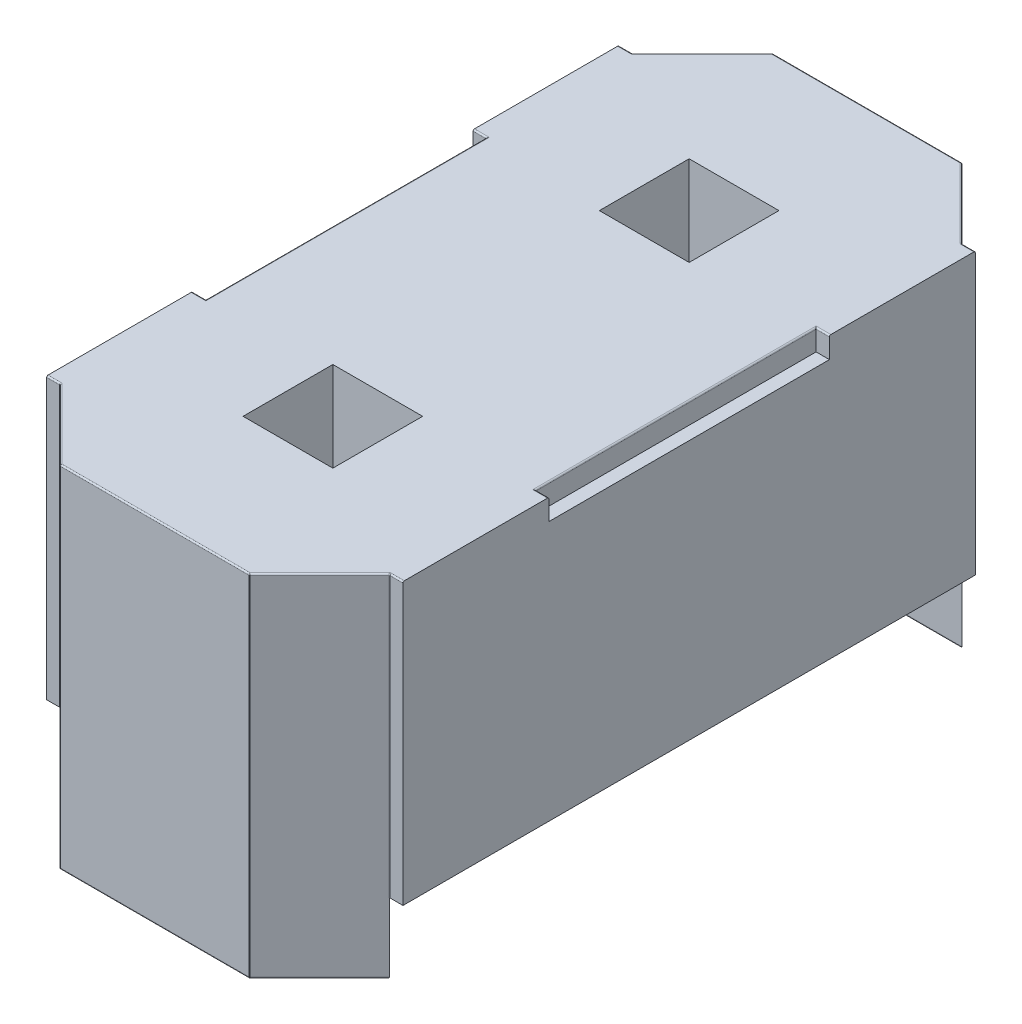
SolidWorks part; units mm, degrees
ref_plane "前视基准面" through (0, 0, 0) normal (0, 0, 1) x (1, 0, 0)
ref_plane "上视基准面" through (0, 0, 0) normal (0, 1, 0) x (1, 0, 0)
ref_plane "右视基准面" through (0, 0, 0) normal (1, 0, 0) x (0, 0, -1)
sketch "Sketch5" plane through (0, 0, 0) normal (0, 1, 0) x (1, 0, 0)
  line L0 (-0.675, 2.54) -> (-1.175, 2.04)
  line L1 (-0.675, 2.54) -> (0.675, 2.54)
  line L2 (-1.175, 2.04) -> (-1.175, -2.04)
  line L3 (-0.675, -2.54) -> (0.675, -2.54)
  line L4 (1.175, 2.04) -> (1.175, -2.04)
  line L7 (0, 2.54) -> (0, -2.54) construction
  line L8 (0.675, 2.54) -> (1.175, 2.04)
  line L9 (-1.175, 0) -> (1.175, 0) construction
  line L10 (0.675, -2.54) -> (1.175, -2.04)
  line L11 (-0.675, -2.54) -> (-1.175, -2.04)
  point P0 (0, 0)
  point P20 (0, 0)
  point P22 (0, -2.54)
  dimension "D1" = 2.35
  dimension "D2" = 5.08
  dimension "D3" = 0.5
  dimension "D4" = 0.5
extrude "Boss-Extrude1" add sketch "Sketch5" along normal blind 2.5
sketch "Sketch7" plane through (0, 2.5, 0) normal (0, 1, 0) x (1, 0, 0)
  line L0 (0, 2.54) -> (0, -2.54) construction
  line L1 (-0.32, 1.59) -> (0.32, 1.59)
  line L2 (-0.32, 1.59) -> (-0.32, 0.95)
  line L3 (-0.32, 0.95) -> (0.32, 0.95)
  line L4 (0.32, 1.59) -> (0.32, 0.95)
  line L5 (-0.32, 1.59) -> (0.32, 0.95) construction
  line L6 (-0.32, 0.95) -> (0.32, 1.59) construction
  line L7 (0.675, 2.54) -> (-0.675, 2.54) construction
  line L8 (-0.675, -2.54) -> (0.675, -2.54) construction
  line L9 (-1.175, 0) -> (1.175, 0) construction
  line L10 (-1.175, 2.04) -> (-1.175, -2.04) construction
  line L11 (1.175, -2.04) -> (1.175, 2.04) construction
  line L12 (-0.32, -0.95) -> (0.32, -0.95)
  line L13 (0.32, -1.59) -> (0.32, -0.95)
  line L14 (-0.32, -1.59) -> (0.32, -1.59)
  line L15 (-0.32, -1.59) -> (-0.32, -0.95)
  line L16 (-0.32, -0.95) -> (0.32, -1.59) construction
  line L17 (-0.32, -1.59) -> (0.32, -0.95) construction
  point P0 (0, 1.27)
  point P17 (0, 0)
  dimension "D1" = 0.64
  dimension "D2" = 0.64
  dimension "D3" = 1.27
extrude "Cut-Extrude1" cut sketch "Sketch7" against normal through all
sketch "Sketch8" plane through (0, 2.5, 0) normal (0, 1, 0) x (1, 0, 0)
  line L0 (0, 2.54) -> (0, -2.54) construction
  line L1 (-1.27, -2.04) -> (-1.175, -2.04)
  line L2 (-1.27, -2.04) -> (-1.27, 2.04)
  line L3 (-1.27, 2.04) -> (-1.175, 2.04)
  line L4 (-1.175, -2.04) -> (-1.175, 2.04)
  line L5 (-1.27, -2.04) -> (-1.175, 2.04) construction
  line L6 (-1.27, 2.04) -> (-1.175, -2.04) construction
  line L7 (-0.675, -2.54) -> (0.675, -2.54) construction
  line L8 (0.675, 2.54) -> (-0.675, 2.54) construction
  line L9 (1.27, 2.04) -> (1.175, -2.04) construction
  line L10 (1.27, -2.04) -> (1.175, 2.04) construction
  line L11 (1.175, -2.04) -> (1.175, 2.04)
  line L12 (1.27, 2.04) -> (1.175, 2.04)
  line L13 (1.27, -2.04) -> (1.27, 2.04)
  line L14 (1.27, -2.04) -> (1.175, -2.04)
  point P0 (-1.2225, 0)
  point P17 (1.2225, 0)
  dimension "D1" = 2.54
extrude "Boss-Extrude2" add sketch "Sketch8" against normal up to surface (2.5 mm away) up to face at (0, 0, -1.27)
sketch "Sketch9" plane through (0, 2.5, 0) normal (0, 1, 0) x (1, 0, 0)
  line L0 (-1.27, 0) -> (1.27, 0) construction
  line L1 (-1.27, 2.04) -> (-1.27, -2.04) construction
  line L2 (1.27, -2.04) -> (1.27, 2.04) construction
  line L3 (0, 2.54) -> (0, -2.54) construction
  line L4 (-1.175, 1) -> (-1.27, 1)
  line L5 (-1.175, 1) -> (-1.175, -1)
  line L6 (-1.175, -1) -> (-1.27, -1)
  line L7 (-1.27, 1) -> (-1.27, -1)
  line L8 (-1.175, 1) -> (-1.27, -1) construction
  line L9 (-1.175, -1) -> (-1.27, 1) construction
  line L10 (0.675, 2.54) -> (-0.675, 2.54) construction
  line L11 (-0.675, -2.54) -> (0.675, -2.54) construction
  line L12 (1.175, -1) -> (1.27, 1) construction
  line L13 (1.175, 1) -> (1.27, -1) construction
  line L14 (1.27, 1) -> (1.27, -1)
  line L15 (1.175, -1) -> (1.27, -1)
  line L16 (1.175, 1) -> (1.175, -1)
  line L17 (1.175, 1) -> (1.27, 1)
  point P6 (-1.2225, 0)
  point P22 (1.2225, 0)
  dimension "D1" = 2
extrude "Cut-Extrude2" cut sketch "Sketch9" against normal blind 0.15
ref_plane "Plane3" through (10, 0, 0) normal (1, 0, 0) x (0, 0, -1)
sketch "Sketch12" plane through (1.27, 0, 0) normal (1, 0, 0) x (0, 0, -1)
  line L0 (0, 2.5) -> (0, 0) construction
  line L2 (1, 2.5) -> (-1, 2.5) construction
  line L7 (1, 2.5) -> (2.04, 2.5) construction
  line L8 (-2.04, 0.5) -> (2.04, 0.5)
  line L9 (-2.04, 0.5) -> (-2.04, 0)
  line L10 (-2.04, 0) -> (2.04, 0)
  line L11 (2.04, 0.5) -> (2.04, 0)
  line L12 (-2.04, 0.5) -> (2.04, 0) construction
  line L13 (-2.04, 0) -> (2.04, 0.5) construction
  line L14 (-2.04, 0) -> (2.04, 0) construction
  line L15 (2.04, 0) -> (2.04, 2.5) construction
  point P5 (0, 0.25)
  dimension "D1" = 2
extrude "Cut-Extrude3" cut sketch "Sketch12" against normal through all both and the other way through all
chamfer "Chamfer1" distance 0.4 angle 45 8 edges at (-0.32, 0.5, -1.27) (0, 0.5, -0.95) (0.32, 0.5, -1.27) (0, 0.5, -1.59) (0, 0.5, 1.59) (0.32, 0.5, 1.27) (0, 0.5, 0.95) (-0.32, 0.5, 1.27)
fillet "Fillet1" radius 0.01 32 edges at (-1.2225, 2.5, -2.04) (-0.925, 2.5, -2.29) (0, 0, -2.54) (0, 2.5, -2.54) (0.925, 2.5, -2.29) (1.2225, 2.5, -2.04) (1.2225, 2.5, -1) (1.175, 2.5, 0) (1.2225, 2.5, 1) (1.2225, 2.5, 2.04) (0.925, 2.5, 2.29) (0, 0, 2.54) (0, 2.5, 2.54) (-0.925, 2.5, 2.29) (-1.2225, 2.5, 2.04) (-1.2225, 2.5, 1) (-1.175, 2.5, 0) (-1.2225, 2.5, -1) (0.925, 0, -2.29) (-0.925, 0, -2.29) (0, 0, -2.04) (-0.925, 0, 2.29) (0.925, 0, 2.29) (0, 0, 2.04) (0.675, 1.25, -2.54) (-0.675, 1.25, -2.54) (-0.675, 1.25, 2.54) (0.675, 1.25, 2.54) (-1.175, 1.5, -2.04) (-1.175, 1.5, 2.04) (1.175, 1.5, -2.04) (1.175, 1.5, 2.04)
